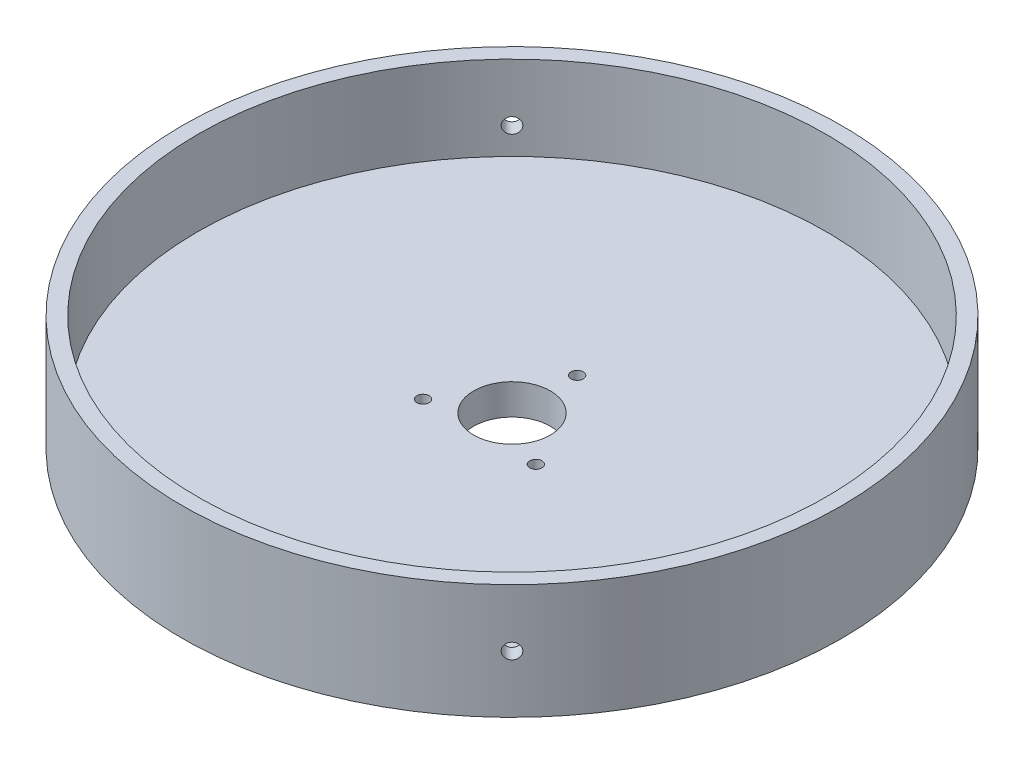
SolidWorks part; units mm, degrees
material "6061-T6 (SS)"
ref_plane "Front Plane" through (0, 0, 0) normal (0, 0, 1) x (1, 0, 0)
ref_plane "Top Plane" through (0, 0, 0) normal (0, 1, 0) x (1, 0, 0)
ref_plane "Right Plane" through (0, 0, 0) normal (1, 0, 0) x (0, 0, -1)
sketch "Sketch1" plane through (0, 0, 0) normal (0, 0, 1) x (1, 0, 0)
  line L0 (5, 0) -> (5, 4)
  line L1 (0, 0) -> (43, 0)
  line L2 (43, 0) -> (43, 15)
  line L3 (43, 15) -> (41, 15)
  line L4 (41, 15) -> (41, 4)
  line L5 (41, 4) -> (0, 4)
  line L6 (0, 4) -> (0, 0)
  dimension "D1" = 41
  dimension "D2" = 2
  dimension "D3" = 15
  dimension "D4" = 5
  dimension "D5" = 4
revolve "Revolve1" add sketch "Sketch1" angle 360 about L6
sketch "Sketch2" plane through (0, 4, 0) normal (0, 1, 0) x (1, 0, 0)
  line L0 (0, 0) -> (0, 8.5) construction
  circle A0 centre (0, 8.5) radius 0.8
  circle A1 centre (7.3612, -4.25) radius 0.8
  circle A2 centre (-7.3612, -4.25) radius 0.8
  dimension "D1" = 1.6
  dimension "D2" = 8.5
  dimension "D3" = 3
extrude "Cut-Extrude1" cut sketch "Sketch2" against normal through all
ref_plane "Plane1" through (0, 0, 0) normal (-0.7071, 0, 0.7071) x (0, -1, 0)
sketch "Sketch3" plane through (0, 0, 0) normal (-0.7071, 0, 0.7071) x (0.7071, 0, 0.7071)
  line L0 (0, 0) -> (0, 7.5) construction
  circle A0 centre (0, 7.5) radius 1
  dimension "D1" = 2
  dimension "D2" = 7.5
extrude "Cut-Extrude2" cut sketch "Sketch3" against normal through all
pattern_circular "CirPattern1" count 4 over 360 about axis through (0, 4, 0) along (0, 1, 0) of "Cut-Extrude2"
